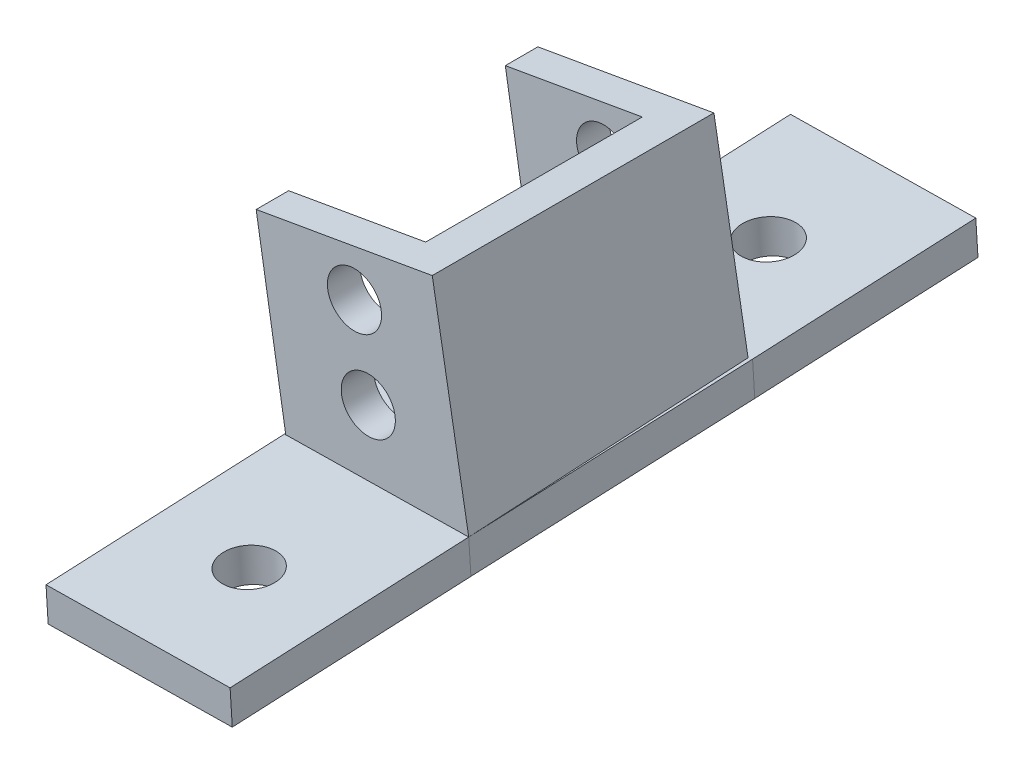
SolidWorks part; units mm, degrees
ref_plane "Front Plane" through (0, 0, 0) normal (0, 0, 1) x (1, 0, 0)
ref_plane "Top Plane" through (0, 0, 0) normal (0, 1, 0) x (1, 0, 0)
ref_plane "Right Plane" through (0, 0, 0) normal (1, 0, 0) x (0, 0, -1)
sketch "Sketch1" plane through (0, 0, 0) normal (0, 0, 1) x (1, 0, 0)
  line L0 (444.2097, 275.3561) -> (448.4842, 250.9436)
  line L1 (448.4842, 250.9436) -> (469.3898, 254.6041)
  line L2 (469.3898, 254.6041) -> (465.1152, 279.0166)
  line L3 (465.1152, 279.0166) -> (444.2097, 275.3561)
  line L4 (458.8626, 254.5214) -> (448.1651, 252.7661)
  line L5 (427.4923, 249.3739) -> (458.8626, 254.5214) construction
  arc A0 (460.5279, 278.2134) -> (463.4772, 270.1621) centre (455.9966, 271.9877) cw
  arc A1 (461.3669, 277.5061) -> (454.7498, 279.5862) centre (455.9966, 271.9877) ccw construction
  arc A2 (463.4772, 270.1621) -> (464.1208, 266.2396) centre (468.4124, 268.9577) ccw
  arc A3 (464.1208, 266.2396) -> (458.8626, 254.5214) centre (457.6159, 262.1197) cw
extrude "Boss-Extrude1" add sketch "Sketch1" against normal blind 29.21 contours A2 A3 L4 L0 L1 L2 L3 A0
sketch "Sketch2" plane through (0, 0, 0) normal (0, 0, 1) x (1, 0, 0)
  line L0 (465.1152, 279.0166) -> (469.3898, 254.6041)
  line L1 (469.3898, 254.6041) -> (448.4842, 250.9436)
  line L2 (448.4842, 250.9436) -> (444.4709, 275.4019)
  line L3 (444.4709, 275.4019) -> (465.1152, 279.0166)
  circle A1 centre (457.6159, 262.1197) radius 3.175
  circle A2 centre (455.9966, 271.9877) radius 3.175
extrude "Boss-Extrude2" add sketch "Sketch2" along normal blind 3.81
sketch "Sketch3" plane through (0, 0, -29.21) normal (0, 0, -1) x (-1, 0, 0)
  line L0 (-460.5279, 278.2134) -> (-444.4709, 275.4019)
  line L1 (-444.4709, 275.4019) -> (-448.1651, 252.7661)
  line L2 (-458.8626, 254.5214) -> (-448.1651, 252.7661)
  arc A0 (-460.5279, 278.2134) -> (-463.4772, 270.1621) centre (-455.9966, 271.9877) ccw
  arc A1 (-463.4772, 270.1621) -> (-464.1208, 266.2396) centre (-468.4124, 268.9577) cw
  arc A2 (-464.1208, 266.2396) -> (-458.8626, 254.5214) centre (-457.6159, 262.1197) ccw
  circle A3 centre (-457.6159, 262.1197) radius 3.175
  circle A4 centre (-455.9966, 271.9877) radius 3.175
extrude "Boss-Extrude3" add sketch "Sketch3" against normal up to surface (3.81 mm away)
ref_plane "Plane1" through (-3.9195, 246.7157, 11.6367) normal (-0.0159, 0.9988, 0.0471) x (0.9999, 0.0158, 0.0007)
sketch "Sketch4" plane through (-3.9195, 246.7157, 11.6367) normal (-0.0159, 0.9988, 0.0471) x (0.9999, 0.0158, 0.0007)
  line L0 (451.769, 41.3633) -> (451.769, 67.5634)
  line L1 (451.769, 67.5634) -> (473.5072, 67.5634)
  line L2 (473.5072, 67.5634) -> (473.5072, 41.3633)
  line L3 (473.5072, 41.3633) -> (473.3689, 8.1896)
  line L4 (473.3689, 8.1896) -> (473.3689, -19.8164)
  line L5 (473.3689, -19.8164) -> (451.769, -19.8164)
  line L6 (451.769, -19.8164) -> (451.769, 41.3633)
  circle A0 centre (462.6967, 54.0309) radius 3.1624
  circle A1 centre (462.6967, -6.9051) radius 3.0913
extrude "Boss-Extrude4" add sketch "Sketch4" against normal blind 4.064
